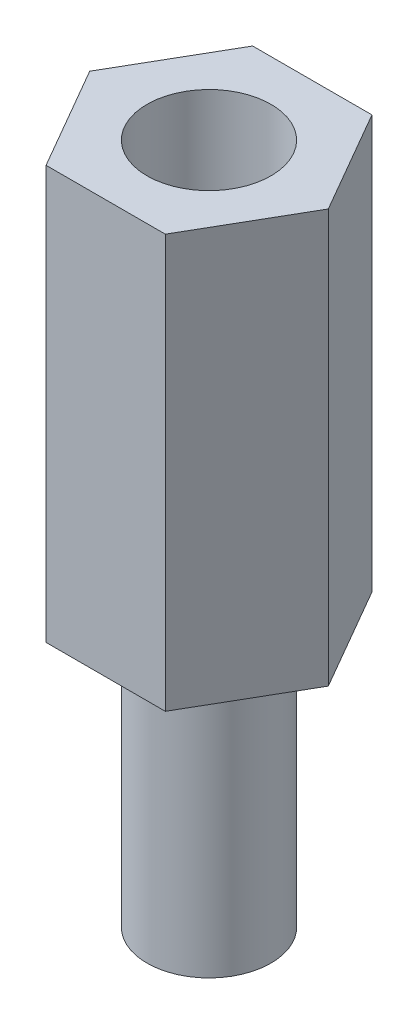
SolidWorks part; units mm, degrees
material "ﾅｲﾛﾝ 101"
ref_plane "正面" through (0, 0, 0) normal (0, 0, 1) x (1, 0, 0)
ref_plane "平面" through (0, 0, 0) normal (0, 1, 0) x (1, 0, 0)
ref_plane "右側面" through (0, 0, 0) normal (1, 0, 0) x (0, 0, -1)
sketch "ｽｹｯﾁ1" plane through (0, 0, 0) normal (0, 1, 0) x (1, 0, 0)
  circle A0 centre (0, 0) radius 1.5
  dimension "D1" = 3
extrude "ﾎﾞｽ - 押し出し1" add sketch "ｽｹｯﾁ1" along normal blind 6.5
sketch "ｽｹｯﾁ2" plane through (0, 6.5, 0) normal (0, 1, 0) x (1, 0, 0)
  line L1 (1.4434, -2.5) -> (2.8868, 0)
  line L2 (2.8868, 0) -> (1.4434, 2.5)
  line L3 (1.4434, 2.5) -> (-1.4434, 2.5)
  line L4 (-1.4434, 2.5) -> (-2.8868, 0)
  line L5 (-2.8868, 0) -> (-1.4434, -2.5)
  line L6 (-1.4434, -2.5) -> (1.4434, -2.5)
  circle A0 centre (0, 0) radius 2.5 construction
  dimension "D1" = 5
extrude "ﾎﾞｽ - 押し出し2" add sketch "ｽｹｯﾁ2" along normal blind 10
sketch "ｽｹｯﾁ3" plane through (0, 16.5, 0) normal (0, 1, 0) x (1, 0, 0)
  circle A0 centre (0, 0) radius 1.5
  dimension "D1" = 3
extrude "ｶｯﾄ - 押し出し1" cut sketch "ｽｹｯﾁ3" against normal blind 6.5
